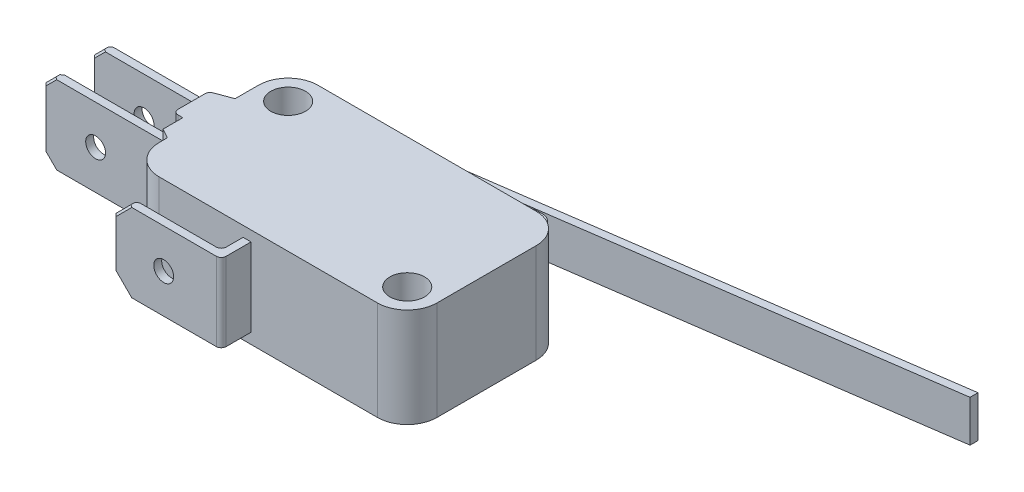
SolidWorks part; units mm, degrees
ref_plane "Front Plane" through (0, 0, 0) normal (0, 0, 1) x (1, 0, 0)
ref_plane "Top Plane" through (0, 0, 0) normal (0, 1, 0) x (1, 0, 0)
ref_plane "Right Plane" through (0, 0, 0) normal (1, 0, 0) x (0, 0, -1)
sketch "Sketch1" plane through (0, 0, 0) normal (0, 1, 0) x (1, 0, 0)
  line L1 (0, 0) -> (28, 0)
  line L2 (0, 0) -> (0, 16)
  line L3 (0, 16) -> (28, 16)
  line L4 (28, 0) -> (28, 16)
  dimension "D1" = 28
  dimension "D2" = 16
extrude "Boss-Extrude1" add sketch "Sketch1" along normal blind 10
sketch "Sketch3" plane through (0, 10, 0) normal (0, 1, 0) x (1, 0, 0)
  line L0 (0, 16) -> (0, 0) construction
  line L1 (28, 16) -> (0, 16) construction
  line L2 (28, 0) -> (28, 16) construction
  line L3 (0, 0) -> (28, 0) construction
  circle A0 centre (2.9, 13.1) radius 1.75
  circle A1 centre (25.1, 2.9) radius 1.75
  dimension "D1" = 2.9
  dimension "D2" = 2.9
  dimension "D3" = 3.5
  dimension "D5" = 2.9
  dimension "D6" = 3.5
  dimension "D4" = 2.9
extrude "Cut-Extrude1" cut sketch "Sketch3" against normal blind 10
fillet "Fillet5" radius 3 2 edges at (28, 5, 0) (0, 5, -16)
fillet "Fillet6" radius 3 2 edges at (28, 5, -16) (0, 5, 0)
sketch "Sketch4" plane through (0, 10, 0) normal (0, 1, 0) x (1, 0, 0)
  line L0 (0, 10.651) -> (-1.9495, 9.9306)
  line L1 (0, 13) -> (0, 3) construction
  line L2 (-1.9495, 9.9306) -> (-1.9495, 6.3575)
  line L3 (-1.9495, 6.3575) -> (-0.9747, 6.3575)
  line L4 (-0.9747, 6.3575) -> (-0.9747, 4.3692)
  line L5 (-0.9747, 4.3692) -> (0.0985, 3.7624)
  line L6 (0, 10.651) -> (0.0985, 3.7624)
  arc A0 (0, 3) -> (3, 0) centre (3, 3) ccw construction
extrude "Boss-Extrude3" add sketch "Sketch4" against normal blind 10
fillet "Fillet7" radius 0.5 1 edges at (-1.9495, 5, -9.9306)
fillet "Fillet8" radius 0.5 1 edges at (-1.9495, 5, -6.3575)
sketch "Sketch5" plane through (-1.9495, 0, 0) normal (-1, 0, 0) x (0, 0, 1)
  line L0 (-10.0514, 0) -> (-10.0514, 10) construction
  line L1 (-10.0514, 9.1) -> (-6.3575, 9.1)
  line L2 (-10.0514, 9.1) -> (-10.0514, 0.9)
  line L3 (-10.0514, 0.9) -> (-6.3575, 0.9)
  line L4 (-6.3575, 9.1) -> (-6.3575, 0.9)
  line L5 (-6.3575, 0) -> (-6.3575, 10) construction
  line L6 (-9.5824, 10) -> (-6.8575, 10) construction
  line L7 (-9.5824, 0) -> (-6.8575, 0) construction
  dimension "D1" = 0.9
  dimension "D2" = 0.9
extrude "Cut-Extrude2" cut sketch "Sketch5" against normal blind 1
sketch "Sketch7" plane through (-0.9495, 0, 0) normal (-1, 0, 0) x (0, 0, 1)
  line L0 (-10.0514, 9.1) -> (-10.0514, 0.9) construction
  line L1 (-10.0514, 8.9519) -> (-9.2514, 8.9519)
  line L2 (-10.0514, 8.9519) -> (-10.0514, 1.0646)
  line L3 (-10.0514, 1.0646) -> (-9.2514, 1.0646)
  line L4 (-9.2514, 8.9519) -> (-9.2514, 1.0646)
  dimension "D1" = 0.8
extrude "Boss-Extrude5" add sketch "Sketch7" along normal blind 12
sketch "Sketch8" plane through (-0.9747, 0, 0) normal (-1, 0, 0) x (0, 0, 1)
  line L0 (-4.3692, 0) -> (-4.3692, 10) construction
  line L1 (-4.3692, 8.9519) -> (-5.1692, 8.9519)
  line L2 (-4.3692, 8.9519) -> (-4.3692, 1.0646)
  line L3 (-4.3692, 1.0646) -> (-5.1692, 1.0646)
  line L4 (-5.1692, 8.9519) -> (-5.1692, 1.0646)
  dimension "D1" = 0.8
extrude "Boss-Extrude6" add sketch "Sketch8" along normal blind 12
chamfer "Chamfer1" distance 1 4 edges at (-12.9495, 1.0646, -9.6514) (-12.9747, 1.0646, -4.7692) (-12.9747, 8.9519, -4.7692) (-12.9495, 8.9519, -9.6514)
chamfer "Chamfer3" distance 0.2 angle 45 12 edges at (-12.4747, 8.4519, -4.3692) (-12.9747, 5.0082, -4.3692) (-12.4747, 1.5646, -4.3692) (-12.4747, 1.5646, -5.1692) (-12.9747, 5.0082, -5.1692) (-12.4747, 8.4519, -5.1692) (-12.4495, 8.4519, -10.0514) (-12.9495, 5.0082, -10.0514) (-12.4495, 1.5646, -10.0514) (-12.4495, 1.5646, -9.2514) (-12.4495, 8.4519, -9.2514) (-12.9495, 5.0082, -9.2514)
sketch "Sketch10" plane through (0, 0, -4.3692) normal (0, 0, 1) x (1, 0, 0)
  line L0 (-12.7747, 7.869) -> (-12.7747, 2.1474) construction
  circle A0 centre (-7.7747, 5.0082) radius 1
  point P4 (-12.7747, 5.0082)
  dimension "D1" = 2
  dimension "D2" = 5
extrude "Cut-Extrude3" cut sketch "Sketch10" against normal blind 8
sketch "Sketch11" plane through (0, 0, 0) normal (0, 0, 1) x (1, 0, 0)
  line L1 (11.4554, 8.9519) -> (12.2554, 8.9519)
  line L2 (11.4554, 8.9519) -> (11.4554, 1.0646)
  line L3 (11.4554, 1.0646) -> (12.2554, 1.0646)
  line L4 (12.2554, 8.9519) -> (12.2554, 1.0646)
  dimension "D1" = 0.8
extrude "Boss-Extrude7" add sketch "Sketch11" along normal blind 3
sketch "Sketch12" plane through (11.4554, 0, 0) normal (-1, 0, 0) x (0, 0, 1)
  line L0 (3, 1.0646) -> (0, 1.0646) construction
  line L1 (3, 8.9519) -> (2.2, 8.9519)
  line L2 (3, 8.9519) -> (3, 1.0646)
  line L3 (3, 1.0646) -> (2.2, 1.0646)
  line L4 (2.2, 8.9519) -> (2.2, 1.0646)
  dimension "D1" = 0.8
extrude "Boss-Extrude8" add sketch "Sketch12" along normal blind 10
fillet "Fillet9" radius 0.5 1 edges at (11.4554, 5.0082, 2.2)
fillet "Fillet10" radius 0.5 1 edges at (12.2554, 5.0082, 3)
chamfer "Chamfer4" distance 1.5 2 edges at (1.4554, 1.0646, 2.6) (1.4554, 8.9519, 2.6)
chamfer "Chamfer5" distance 0.2 angle 45 6 edges at (2.2054, 8.2019, 2.2) (1.4554, 5.0082, 2.2) (2.2054, 1.8146, 2.2) (2.2054, 1.8146, 3) (2.2054, 8.2019, 3) (1.4554, 5.0082, 3)
sketch "Sketch13" plane through (0, 0, 3) normal (0, 0, 1) x (1, 0, 0)
  line L1 (1.4554, 2.5646) -> (1.4554, 7.4519) construction
  circle A0 centre (6.4554, 5.0082) radius 1
  dimension "D2" = 2
  dimension "D1" = 5
extrude "Cut-Extrude4" cut sketch "Sketch13" against normal blind 1
sketch "Sketch14" plane through (0, 0, -16) normal (0, 0, -1) x (-1, 0, 0)
  line L0 (-28, 0) -> (-28, 10) construction
  line L1 (-21.0856, 2.9093) -> (-23.7, 2.9093)
  line L2 (-21.0856, 2.9093) -> (-21.0856, 7.0907)
  line L3 (-21.0856, 7.0907) -> (-23.7, 7.0907)
  line L4 (-23.7, 2.9093) -> (-23.7, 7.0907)
  line L5 (-21.0856, 2.9093) -> (-23.7, 7.0907) construction
  line L6 (-21.0856, 7.0907) -> (-23.7, 2.9093) construction
  point P0 (-22.3928, 5)
  dimension "D1" = 4.3
extrude "Boss-Extrude10" add sketch "Sketch14" along normal blind 3
fillet "Fillet12" radius 1 2 edges at (21.0856, 5, -19) (23.7, 5, -19)
sketch "Sketch17" plane through (0, 0, -16) normal (0, 0, -1) x (-1, 0, 0)
  line L1 (-10.6879, 2.9093) -> (-11.4879, 2.9093)
  line L2 (-10.6879, 2.9093) -> (-10.6879, 7.0907)
  line L3 (-10.6879, 7.0907) -> (-11.4879, 7.0907)
  line L4 (-11.4879, 2.9093) -> (-11.4879, 7.0907)
  line L5 (-10.6879, 2.9093) -> (-11.4879, 7.0907) construction
  line L6 (-10.6879, 7.0907) -> (-11.4879, 2.9093) construction
  point P0 (-11.0879, 5)
  dimension "D1" = 0.8
extrude "Boss-Extrude11" add sketch "Sketch17" along normal blind 2.4
sketch "Sketch18" plane through (0, 7.0907, 0) normal (0, 1, 0) x (1, 0, 0)
  line L0 (11.4879, 18.4) -> (11.4879, 17.5997)
  line L1 (11.4879, 18.4) -> (11.4879, 16) construction
  line L2 (11.4879, 17.5997) -> (60.1886, 24.5343)
  line L3 (60.1886, 24.5343) -> (60.1886, 25.3346)
  line L4 (60.1886, 25.3346) -> (10.6879, 18.2861)
  line L5 (10.6879, 18.4) -> (10.6879, 16) construction
  line L6 (25, 16) -> (3, 16) construction
  line M2 (11.4879, 16) -> (11.4879, 18.4)
  dimension "D1" = 50
  dimension "D2" = 0.8003
  dimension "D3" = 8.104
extrude "Boss-Extrude12" add sketch "Sketch18" against normal blind 4.18 contours L3 L4 L2 M2
sketch "Sketch20" plane through (0, 7.0907, 0) normal (0, 1, 0) x (1, 0, 0)
  line L0 (11.9569, 18.4642) -> (10.6879, 18.2835)
  line L2 (10.6879, 18.4) -> (10.6879, 16) construction
  line L3 (10.6879, 18.2835) -> (10.6879, 18.4)
  line L4 (10.6879, 18.4) -> (11.9569, 18.4642)
extrude "Cut-Extrude9" cut sketch "Sketch20" against normal blind 5
fillet "Fillet14" radius 1 1 edges at (11.4879, 5.0007, -17.5997)
